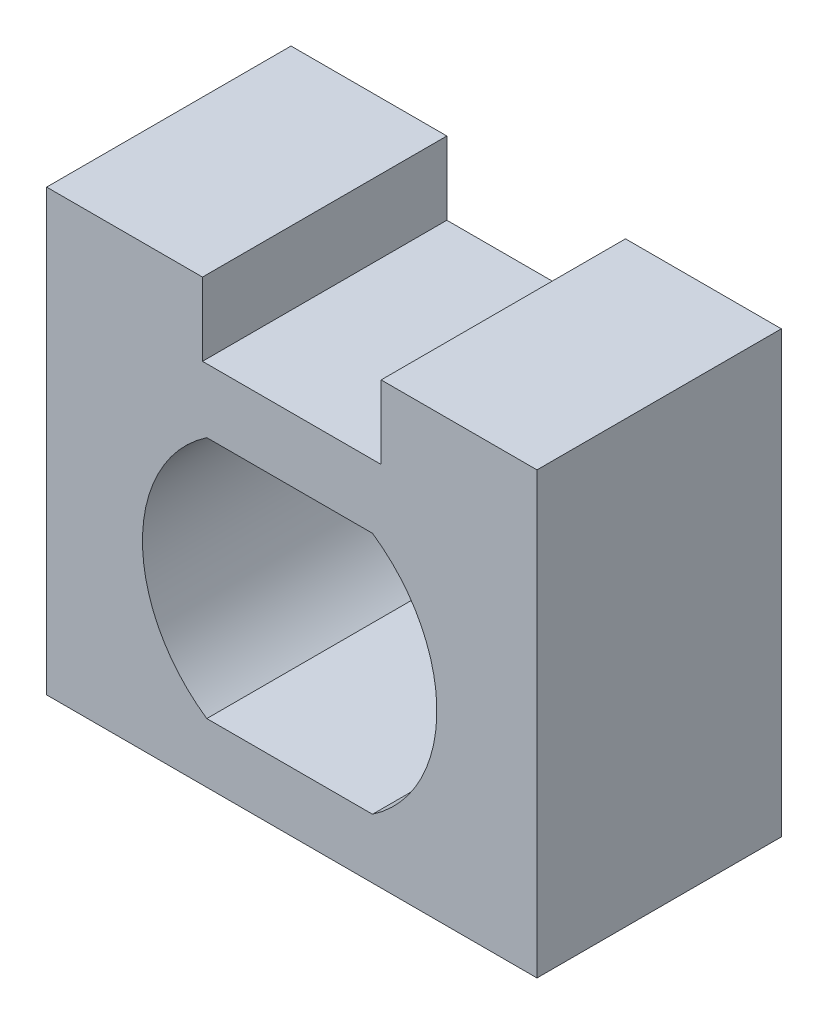
SolidWorks part; units mm, degrees
ref_plane "Front" through (0, 0, 0) normal (0, 0, 1) x (1, 0, 0)
ref_plane "Top" through (0, 0, 0) normal (0, 1, 0) x (1, 0, 0)
ref_plane "Right" through (0, 0, 0) normal (1, 0, 0) x (0, 0, -1)
sketch "Sketch1" plane through (0, 0, 0) normal (0, 0, 1) x (1, 0, 0)
  line L0 (0, 0) -> (20.066, 0)
  line L1 (0, 0) -> (0, 15.0114)
  line L2 (10.033, 15.0114) -> (10.033, 18.0086) construction
  line L3 (20.066, 15.0114) -> (20.066, 0)
  line L4 (0, 15.0114) -> (0, 17.998)
  line L5 (10.033, 0) -> (10.033, 18.0086) construction
  line L6 (6.3776, 17.998) -> (6.3776, 15.0114)
  line L7 (13.6884, 15.0114) -> (13.6884, 18.0086)
  line L8 (0, 17.998) -> (6.3776, 17.998)
  line L9 (6.3776, 15.0114) -> (13.6884, 15.0114)
  line L10 (13.6884, 18.0086) -> (20.066, 18.0086)
  line L11 (20.066, 18.0086) -> (20.066, 15.0114)
  line L24 (9.9441, 12.3952) -> (6.5532, 12.3952)
  line L25 (6.5532, 12.3952) -> (9.9441, 12.3952)
  line L26 (13.335, 12.3952) -> (9.9441, 12.3952)
  line L27 (9.9441, 2.4384) -> (6.5532, 2.4384)
  line L28 (9.9441, 2.4384) -> (13.335, 2.4384)
  arc A2 (6.5532, 12.3952) -> (6.5532, 2.4384) centre (9.9441, 7.4168) ccw
  arc A3 (13.335, 2.4384) -> (13.335, 12.3952) centre (9.9441, 7.4168) ccw
  dimension "D9" = 10.1219
  dimension "D11" = 3.3909
  dimension "D14" = 6.0235
  dimension "D1" = 20.066
  dimension "D2" = 15.0114
  dimension "D3" = 6.3776
  dimension "D4" = 2.9866
  dimension "D5" = 7.3108
  dimension "D6" = 6.3776
  dimension "D7" = 2.9972
  dimension "D8" = 2.9972
  dimension "D10" = 9.9568
  dimension "D12" = 3.3909
  dimension "D13" = 2.4384
  dimension "D15" = 3.3909
extrude "Boss-Extrude1" add sketch "Sketch1" along normal blind 10
